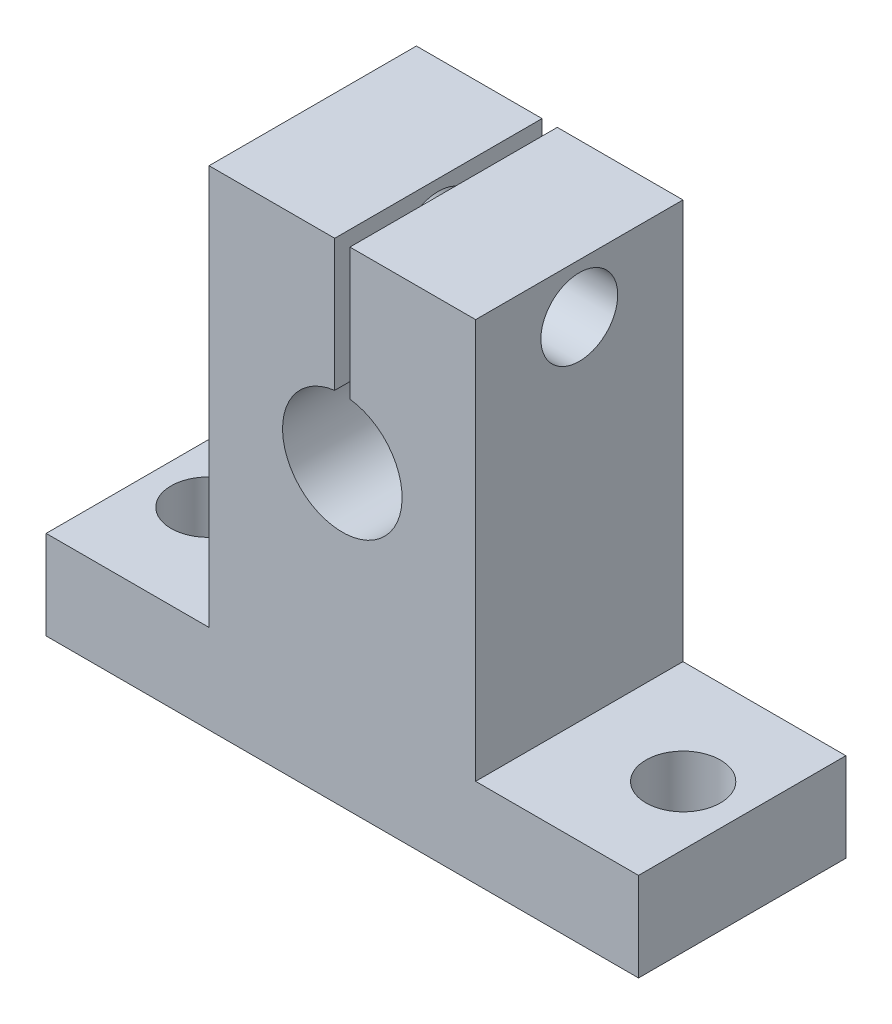
SolidWorks part; units mm, degrees
ref_plane "Alzado" through (0, 0, 0) normal (0, 0, 1) x (1, 0, 0)
ref_plane "Planta" through (0, 0, 0) normal (0, 1, 0) x (1, 0, 0)
ref_plane "Vista lateral" through (0, 0, 0) normal (1, 0, 0) x (0, 0, -1)
sketch "Croquis1" plane through (0, 0, 0) normal (0, 0, 1) x (1, 0, 0)
  line L1 (-2.0004, 17.6992) -> (15.9996, 17.6992)
  line L2 (-2.0004, 17.6992) -> (-2.0004, -9.3008)
  line L3 (-2.0004, -15.3008) -> (15.9996, -15.3008)
  line L4 (15.9996, 17.6992) -> (15.9996, -9.3008)
  line L5 (15.9996, -15.3008) -> (26.9996, -15.3008)
  line L7 (15.9996, -9.3008) -> (26.9996, -9.3008)
  line L8 (26.9996, -15.3008) -> (26.9996, -9.3008)
  line L9 (-2.0004, -15.3008) -> (-13.0004, -15.3008)
  line L11 (-2.0004, -9.3008) -> (-13.0004, -9.3008)
  line L12 (-13.0004, -15.3008) -> (-13.0004, -9.3008)
  dimension "D1" = 33
  dimension "D2" = 18
  dimension "D3" = 11
  dimension "D4" = 6
  dimension "D5" = 11
extrude "Saliente-Extruir1" add sketch "Croquis1" along normal blind 14 contours L9 L12 L11 L2 L1 L4 L7 L8 L5 L3
sketch "Croquis2" plane through (0, 0, 14) normal (0, 0, 1) x (1, 0, 0)
  line L0 (6.9996, -15.3008) -> (6.9996, 4.8031) construction
  line L1 (-13.0004, -15.3008) -> (26.9996, -15.3008) construction
  circle A0 centre (6.9996, 4.8031) radius 4.0356
extrude "Cortar-Extruir1" cut sketch "Croquis2" against normal blind 14
sketch "Croquis4" plane through (0, 0, 14) normal (0, 0, 1) x (1, 0, 0)
  line L0 (6.9996, -15.3008) -> (6.9996, 0.7674) construction
  line L1 (-13.0004, -15.3008) -> (26.9996, -15.3008) construction
  line L2 (6.9996, -11.9058) -> (-9.0658, -11.9058) construction
  line L3 (6.9996, -11.9058) -> (23.065, -11.9058) construction
  circle A0 centre (6.9996, 4.8031) radius 4.0356 construction
sketch "Croquis5" plane through (0, -9.3008, 0) normal (0, 1, 0) x (1, 0, 0)
  circle A0 centre (-9.0658, -7) radius 2.4977
sketch "Croquis7" plane through (0, -9.3008, 0) normal (0, 1, 0) x (1, 0, 0)
  line L0 (-9.0658, -7) -> (-13.0004, -7) construction
  line L1 (-13.0004, -14) -> (-13.0004, 0) construction
  line L2 (26.9996, -7) -> (23.0145, -7) construction
  line L3 (26.9996, -14) -> (26.9996, 0) construction
  circle A0 centre (23.0145, -7) radius 2.5149
extrude "Cortar-Extruir2" cut sketch "Croquis5" against normal blind 14 contours A0
extrude "Cortar-Extruir3" cut sketch "Croquis7" against normal blind 14 contours A0
sketch "Croquis8" plane through (0, 0, 14) normal (0, 0, 1) x (1, 0, 0)
  line L1 (6.4852, 18.6554) -> (7.5141, 18.6554)
  line L2 (6.4852, 18.6554) -> (6.4852, 8.216)
  line L3 (6.4852, 8.216) -> (7.5141, 8.216)
  line L4 (7.5141, 18.6554) -> (7.5141, 8.216)
  line L5 (6.4852, 18.6554) -> (7.5141, 8.216) construction
  line L6 (6.4852, 8.216) -> (7.5141, 18.6554) construction
  point P0 (6.9996, 13.4357)
extrude "Cortar-Extruir4" cut sketch "Croquis8" against normal blind 14
sketch "Croquis9" plane through (-2.0004, 0, 0) normal (-1, 0, 0) x (0, 0, 1)
  circle A0 centre (7, 14.3513) radius 2.594
extrude "Cortar-Extruir5" cut sketch "Croquis9" against normal through all contours A0
